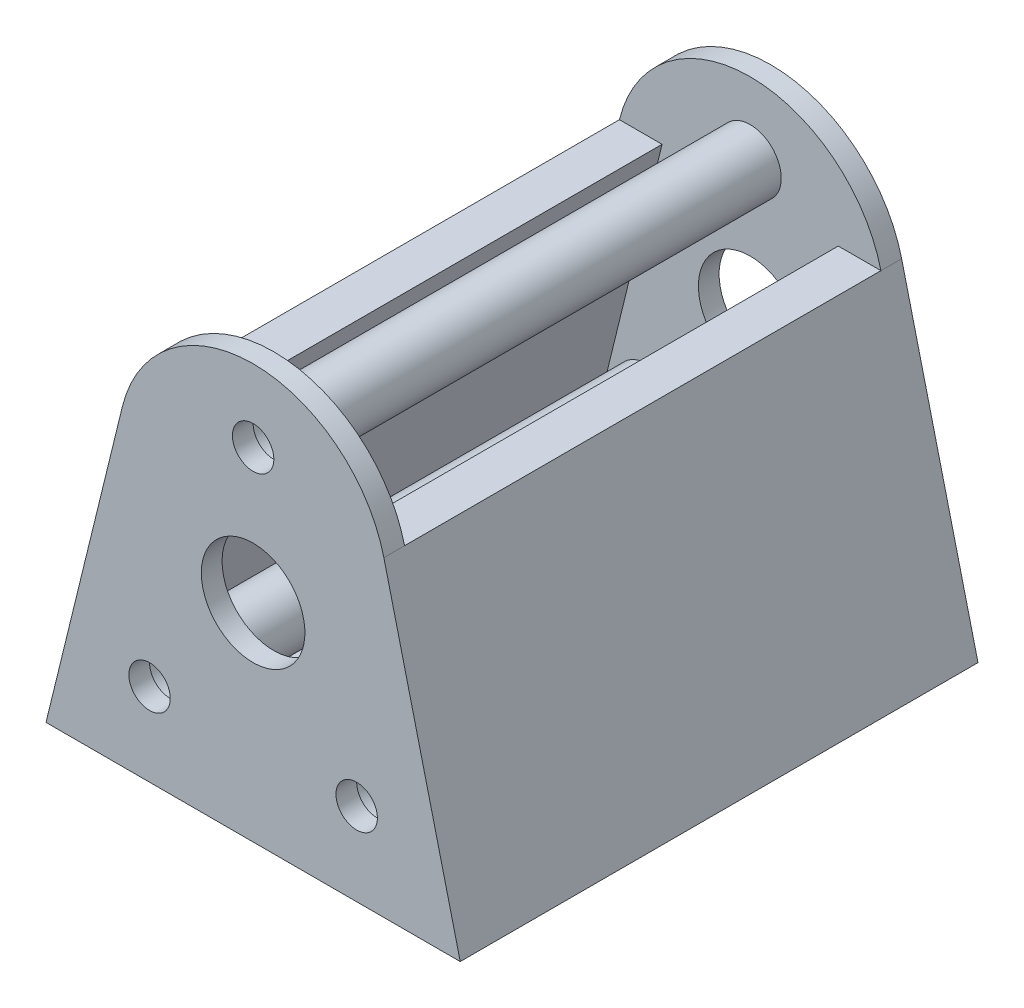
SolidWorks part; units mm, degrees
ref_plane "Front Plane" through (0, 0, 0) normal (0, 0, 1) x (1, 0, 0)
ref_plane "Top Plane" through (0, 0, 0) normal (0, 1, 0) x (1, 0, 0)
ref_plane "Right Plane" through (0, 0, 0) normal (1, 0, 0) x (0, 0, -1)
sketch "Sketch1" plane through (0, 0, 0) normal (0, 0, 1) x (1, 0, 0)
  line L0 (-20, 0) -> (20, 0)
  line L1 (0, 0) -> (0, 40) construction
  line L2 (20, 0) -> (12.6265, 30.0937)
  line L3 (-20, 0) -> (-12.6265, 30.0937)
  line L4 (-10, 8) -> (10, 8) construction
  arc A0 (12.6265, 30.0937) -> (-12.6265, 30.0937) centre (0, 27) ccw
  circle A1 centre (0, 20) radius 5
  circle A2 centre (0, 33) radius 2
  circle A3 centre (10, 8) radius 2
  circle A4 centre (-10, 8) radius 2
  point P4 (0, 0)
  point P17 (0, 8)
  dimension "D3" = 26
  dimension "D4" = 10
  dimension "D5" = 7
  dimension "D6" = 4
  dimension "D7" = 4
  dimension "D8" = 20
  dimension "D1" = 40
  dimension "D2" = 40
  dimension "D9" = 8
extrude "Boss-Extrude1" add sketch "Sketch1" along normal blind 2
ref_plane "Plane1" through (0, 0, 50) normal (0, 0, -1) x (-1, 0, 0)
sketch "Sketch2" plane through (0, 0, 50) normal (0, 0, -1) x (-1, 0, 0)
  line L3 (-12.6265, 30.0937) -> (-20, 0)
  line L4 (20, 0) -> (12.6265, 30.0937)
  line L5 (-20, 0) -> (20, 0)
  line L6 (-12.6265, 30.0937) -> (-20, 0)
  line L7 (20, 0) -> (12.6265, 30.0937)
  line L8 (-20, 0) -> (20, 0)
  circle A0 centre (-10, 8) radius 2 construction
  arc A1 (12.6265, 30.0937) -> (-12.6265, 30.0937) centre (0, 27) ccw
  arc A2 (12.6265, 30.0937) -> (-12.6265, 30.0937) centre (0, 27) ccw
  circle A3 centre (0, 20) radius 5
  circle A4 centre (0, 20) radius 5
  circle A5 centre (0, 33) radius 2
  circle A6 centre (0, 33) radius 2
  circle A7 centre (10, 8) radius 2
  circle A8 centre (10, 8) radius 2
  circle A9 centre (-10, 8) radius 2
  dimension "D1" = 0
  dimension "D2" = 0
  dimension "D3" = 0
  dimension "D4" = 0
extrude "Boss-Extrude2" add sketch "Sketch2" along normal blind 2 separate body
sketch "Sketch4" plane through (0, 0, 48) normal (0, 0, -1) x (-1, 0, 0)
  line L0 (0, 0) -> (0, 22.054) construction
  line L1 (-20, 0) -> (20, 0) construction
  circle A0 centre (10, 8) radius 3
  circle A1 centre (10, 8) radius 2.5
  circle A2 centre (0, 33) radius 3
  circle A3 centre (0, 33) radius 2.5
  circle A4 centre (-10, 8) radius 2.5
  circle A5 centre (-10, 8) radius 3
  dimension "D1" = 6
  dimension "D3" = 6
  dimension "D2" = 0.5
  dimension "D4" = 0.5
extrude "Boss-Extrude3" add sketch "Sketch4" along normal up to surface (46 mm away) up to face at (12, 8, 2)
sketch "Sketch5" plane through (0, 0, 48) normal (0, 0, -1) x (-1, 0, 0)
  line L0 (-20, 0) -> (20, 0) construction
  line L1 (-20, 0) -> (20, 0)
  line L2 (19.0199, 4) -> (-19.0199, 4)
  line L3 (20, 0) -> (12.6265, 30.0937) construction
  line L4 (-12.6265, 30.0937) -> (-20, 0) construction
  line L5 (19.0199, 4) -> (20, 0)
  line L6 (-19.0199, 4) -> (-20, 0)
  dimension "D1" = 4
extrude "Boss-Extrude4" add sketch "Sketch5" along normal up to surface (46 mm away) up to face at (13, 8, 2)
sketch "Sketch6" plane through (0, 0, 48) normal (0, 0, -1) x (-1, 0, 0)
  line L0 (19.0199, 4) -> (12.6265, 30.0937) construction
  line L1 (19.0199, 4) -> (12.6265, 30.0937)
  line L2 (14.9016, 4) -> (8.5082, 30.0937)
  line L3 (19.0199, 4) -> (14.9016, 4)
  line L4 (12.6265, 30.0937) -> (8.5082, 30.0937)
  line L5 (15.1348, 3.0481) -> (8.7414, 29.1418) construction
  line L6 (0, 0) -> (0, 27.7626) construction
  line L7 (-19.0199, 4) -> (-14.9016, 4)
  line L8 (-19.0199, 4) -> (-12.6265, 30.0937)
  line L9 (-12.6265, 30.0937) -> (-8.5082, 30.0937)
  line L10 (-14.9016, 4) -> (-8.5082, 30.0937)
  dimension "D1" = 4
extrude "Boss-Extrude5" add sketch "Sketch6" along normal up to surface (46 mm away) up to face at (13, 8, 2)
sketch "Sketch7" plane through (0, 0, 0) normal (0, 0, -1) x (-1, 0, 0)
  circle A0 centre (0, 20) radius 3.0979
ref_plane "Plane2" through (0, 20, 0) normal (0, 1, 0) x (1, 0, 0)
sketch "Sketch8" plane through (0, 20, 0) normal (0, 1, 0) x (1, 0, 0)
  line L0 (0, 0) -> (0, -25) construction
sketch "Sketch9" plane through (0, 0, 0) normal (0, -1, 0) x (1, 0, 0)
  line L0 (0, 0) -> (0, 50) construction
  line L1 (20, 50) -> (-20, 50) construction
  line L2 (0, 25) -> (-20, 25) construction
  line L3 (-20, 50) -> (-20, 0) construction
  line L4 (-10, 25) -> (-10, 0) construction
  line L5 (-20, 0) -> (20, 0) construction
  circle A0 centre (-10, 12.5) radius 5
  circle A1 centre (-10, 12.5) radius 2.5
  circle A2 centre (-10, 37.5) radius 2.5
  circle A3 centre (-10, 37.5) radius 5
  circle A4 centre (10, 12.5) radius 2.5
  circle A5 centre (10, 12.5) radius 5
  circle A6 centre (10, 37.5) radius 2.5
  circle A7 centre (10, 37.5) radius 5
  dimension "D1" = 10
  dimension "D2" = 5
extrude "Boss-Extrude6" add sketch "Sketch9" along normal blind 5
